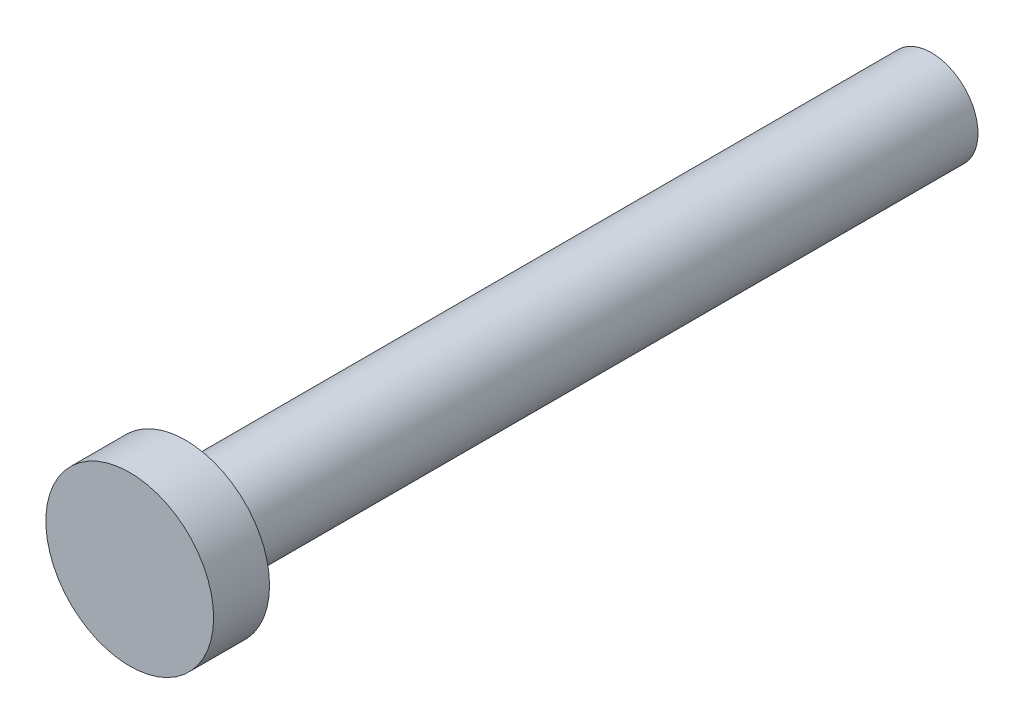
SolidWorks part; units mm, degrees
ref_plane "Front Plane" through (0, 0, 0) normal (0, 0, 1) x (1, 0, 0)
ref_plane "Top Plane" through (0, 0, 0) normal (0, 1, 0) x (1, 0, 0)
ref_plane "Right Plane" through (0, 0, 0) normal (1, 0, 0) x (0, 0, -1)
other "Configuration Table"
sketch "Sketch2" plane through (0, 0, 0) normal (0, 0, 1) x (1, 0, 0)
  circle A0 centre (0, 0) radius 2.5
extrude "M5_reference_shank" add sketch "Sketch2" along normal blind 40 from offset 0
sketch "Sketch3" plane through (0, 0, 0) normal (0, 0, 1) x (1, 0, 0)
  circle A0 centre (0, 0) radius 4.5
extrude "Reference_head" add sketch "Sketch3" along normal blind 3 from offset 40
